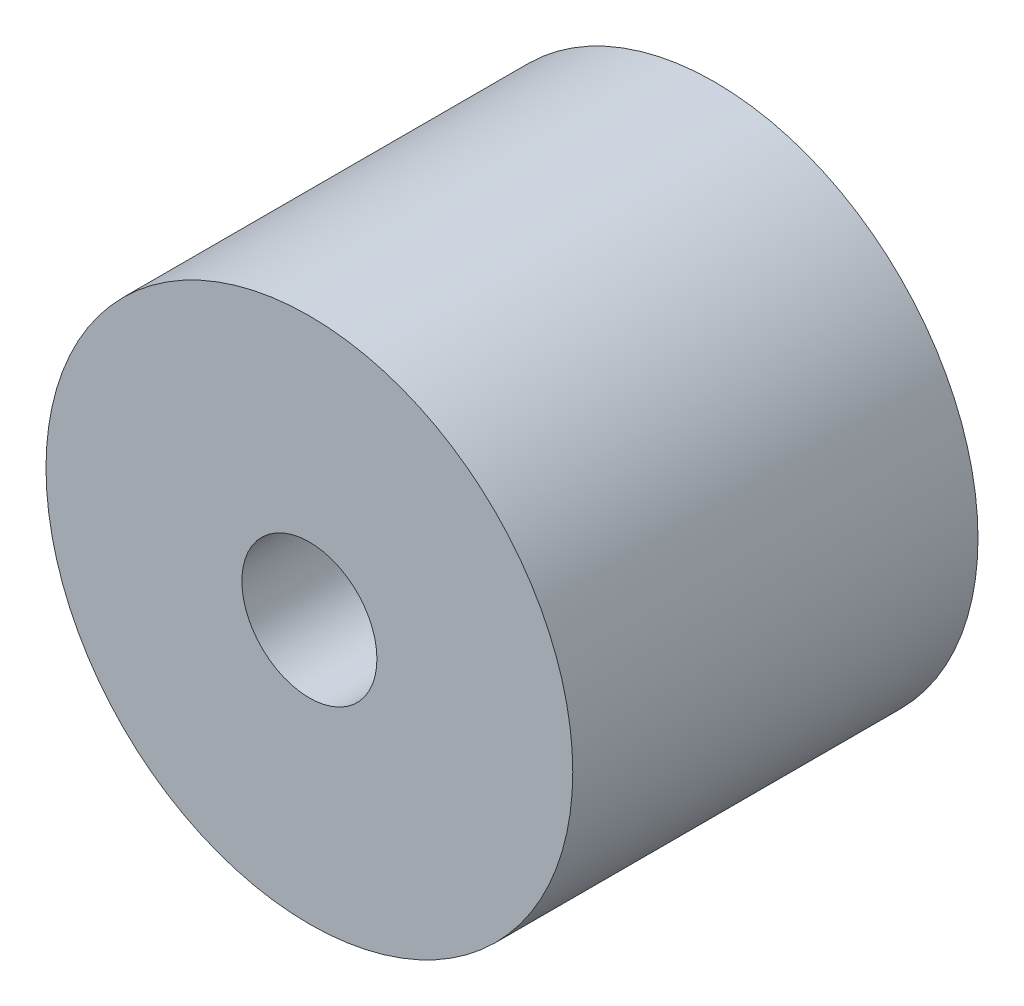
SolidWorks part; units mm, degrees
ref_plane "Front Plane" through (0, 0, 0) normal (0, 0, 1) x (1, 0, 0)
ref_plane "Top Plane" through (0, 0, 0) normal (0, 1, 0) x (1, 0, 0)
ref_plane "Right Plane" through (0, 0, 0) normal (1, 0, 0) x (0, 0, -1)
sketch "Sketch1" plane through (0, 0, 0) normal (0, 0, 1) x (1, 0, 0)
  circle A0 centre (0, 0) radius 19.5
  dimension "D1" = 39
extrude "Boss-Extrude1" add sketch "Sketch1" along normal mid plane 30 contours A0
sketch "Sketch2" plane through (0, 0, 15) normal (0, 0, 1) x (1, 0, 0)
  circle A0 centre (0, 0) radius 5
  dimension "D1" = 10
extrude "Cut-Extrude1" cut sketch "Sketch2" against normal blind 32
